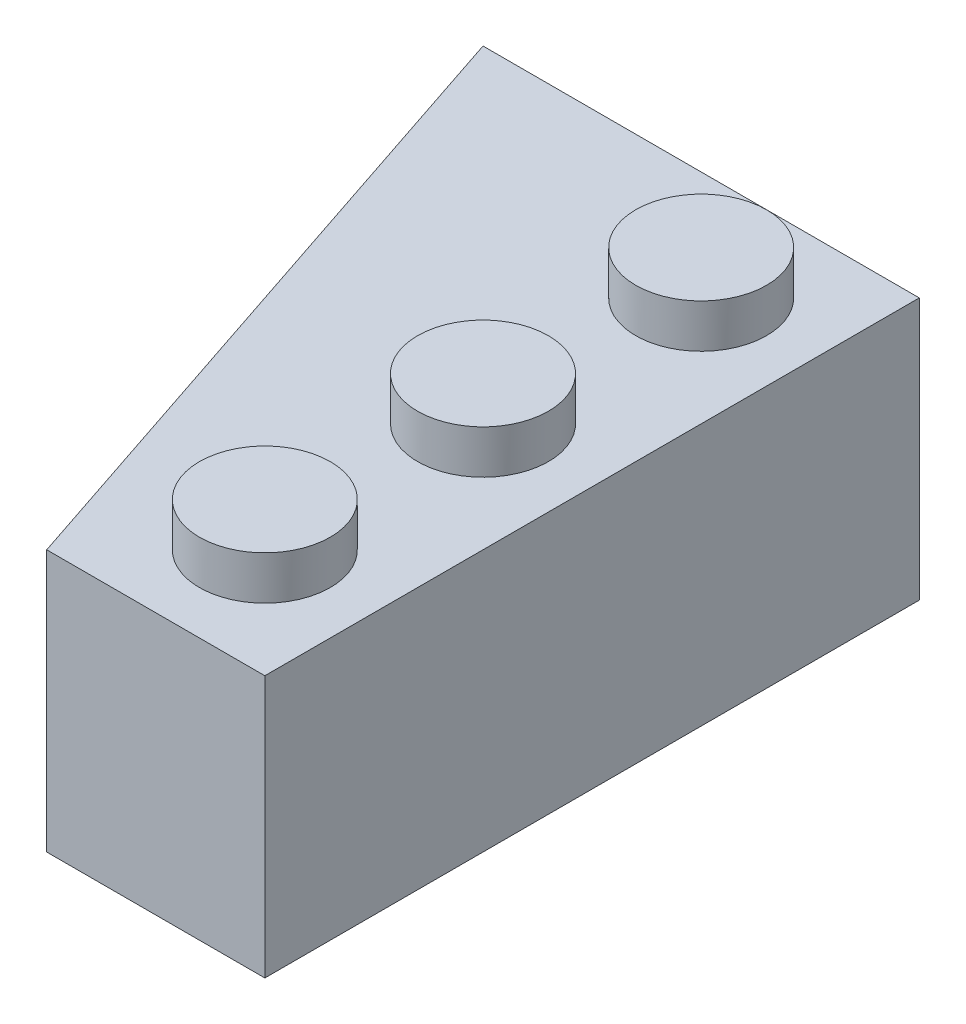
SolidWorks part; units mm, degrees
ref_plane "Front Plane" through (0, 0, 0) normal (0, 0, 1) x (1, 0, 0)
ref_plane "Top Plane" through (0, 0, 0) normal (0, 1, 0) x (1, 0, 0)
ref_plane "Right Plane" through (0, 0, 0) normal (1, 0, 0) x (0, 0, -1)
sketch "Sketch1" plane through (0, 0, 0) normal (0, 1, 0) x (1, 0, 0)
  line L0 (0, 0) -> (-8, 0)
  line L1 (-8, 0) -> (-16, 24)
  line L2 (-16, 24) -> (0, 24)
  line L3 (0, 24) -> (0, 0)
  dimension "D1" = 8
  dimension "D2" = 24
  dimension "D3" = 16
extrude "Boss-Extrude1" add sketch "Sketch1" along normal blind 9.6
sketch "Sketch2" plane through (0, 9.6, 0) normal (0, 1, 0) x (1, 0, 0)
  line L0 (-4, 0) -> (-4, 4) construction
  line L1 (-8, 0) -> (0, 0) construction
  circle A0 centre (-4, 4) radius 2.4
  dimension "D2" = 4.8
  dimension "D1" = 4
extrude "Boss-Extrude2" add sketch "Sketch2" along normal blind 1.6
pattern_linear "LPattern1" count 3 spacing 8 along (0, 0, -1) of "Boss-Extrude2"
shell "Shell1" thickness 1.6
sketch "Sketch3" plane through (0, 0, 0) normal (0, -1, 0) x (1, 0, 0)
  line L0 (-16, -24) -> (-12, -24) construction
  line L1 (0, -24) -> (-16, -24) construction
  line L2 (-12, -24) -> (-12, -20) construction
  line L3 (-12, -20) -> (-12, -12) construction
  circle A0 centre (-12, -12) radius 2.4
  circle A1 centre (-12, -20) radius 2.4
  dimension "D3" = 4.8
  dimension "D5" = 4.8
  dimension "D1" = 4
  dimension "D2" = 4
  dimension "D4" = 8
extrude "Cut-Extrude1" cut sketch "Sketch3" against normal blind 1.6
